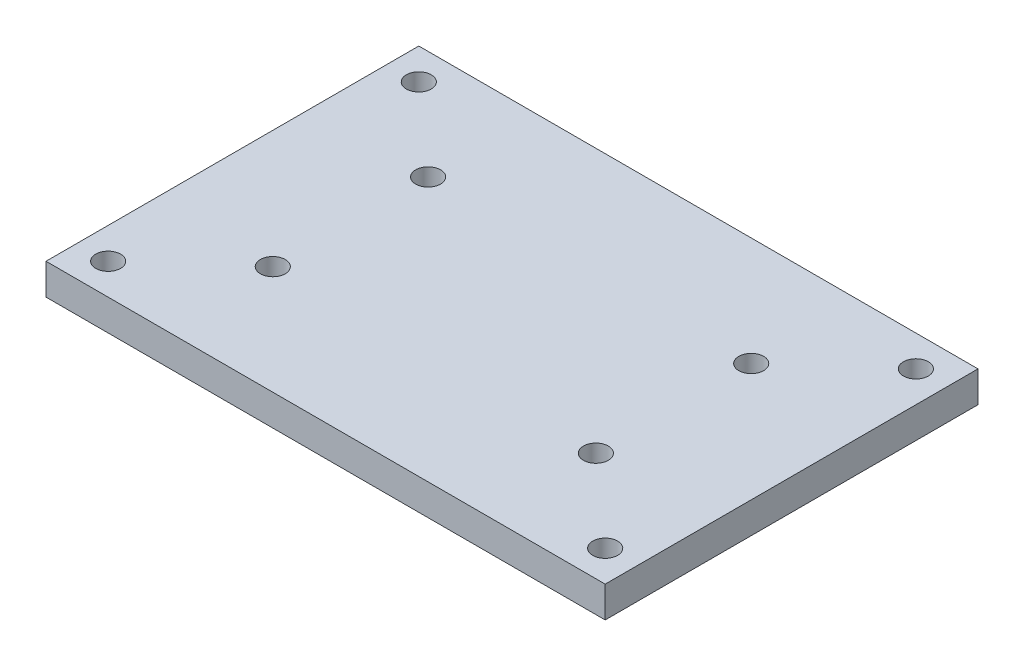
SolidWorks part; units mm, degrees
ref_plane "Front Plane" through (0, 0, 0) normal (0, 0, 1) x (1, 0, 0)
ref_plane "Top Plane" through (0, 0, 0) normal (0, 1, 0) x (1, 0, 0)
ref_plane "Right Plane" through (0, 0, 0) normal (1, 0, 0) x (0, 0, -1)
sketch "草图1" plane through (0, 0, 0) normal (0, 1, 0) x (1, 0, 0)
  line L0 (0, 41.682) -> (0, -51.3594) construction
  line L1 (-74.3553, 0) -> (56.165, 0) construction
  line L2 (45, -30) -> (-45, -30)
  line L3 (45, -30) -> (45, 30)
  line L4 (45, 30) -> (-45, 30)
  line L5 (-45, -30) -> (-45, 30)
  line L6 (45, -30) -> (-45, 30) construction
  line L7 (45, 30) -> (-45, -30) construction
  circle A0 centre (-40, 25) radius 2
  circle A1 centre (40, 25) radius 2
  circle A2 centre (40, -25) radius 2
  circle A3 centre (-40, -25) radius 2
  circle A4 centre (-26, 12.5) radius 2
  circle A5 centre (26, 12.5) radius 2
  circle A6 centre (26, -12.5) radius 2
  circle A7 centre (-26, -12.5) radius 2
  point P2 (0, 0)
  dimension "D5" = 4
  dimension "D6" = 4
  dimension "D9" = 4
  dimension "D1" = 90
  dimension "D2" = 60
  dimension "D3" = 80
  dimension "D4" = 40
  dimension "D7" = 5
  dimension "D8" = 5
  dimension "D10" = 26
  dimension "D11" = 12.5
extrude "凸台-拉伸1" add sketch "草图1" along normal blind 5
